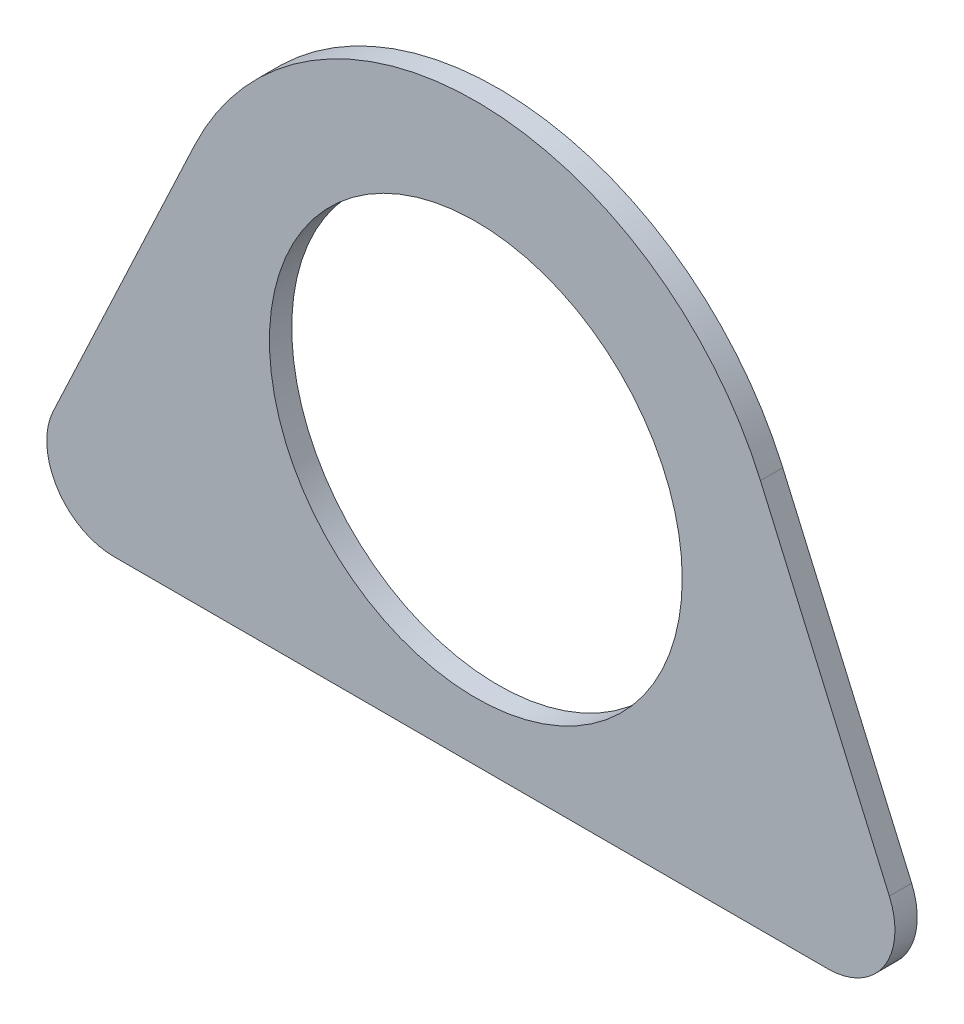
SolidWorks part; units mm, degrees
material "AISI 4340 Steel, annealed"
ref_plane "Front Plane" through (0, 0, 0) normal (0, 0, 1) x (1, 0, 0)
ref_plane "Top Plane" through (0, 0, 0) normal (0, 1, 0) x (1, 0, 0)
ref_plane "Right Plane" through (0, 0, 0) normal (1, 0, 0) x (0, 0, -1)
sketch "Sketch1" plane through (0, 0, 162) normal (0, 0, 1) x (1, 0, 0)
  line L0 (-45.305, 70) -> (-20, 70) construction
  line L1 (20, 70) -> (45.305, 70) construction
  line L2 (100.6815, -15) -> (40.766, 122.3166) construction
  line L3 (-35.2893, 123.3691) -> (-100.2791, -15) construction
  line L4 (-45.305, 70) -> (-20, 70)
  line L5 (20, 70) -> (45.305, 70)
  line L6 (58.0959, 82.5993) -> (40.766, 122.3166)
  line L7 (-35.2893, 123.3691) -> (-54.3317, 82.8261)
  line L8 (-45.305, 70) -> (-46.1855, 70)
  line L9 (-20, 70) -> (20, 70)
  line L10 (45.305, 70) -> (49.8469, 70)
  circle A0 centre (2.5, 105.6188) radius 27.75
  circle A1 centre (2.5, 105.6188) radius 31.75 construction
  circle A2 centre (2.5, 105.62) radius 31.75 construction
  arc A3 (40.766, 122.3166) -> (-35.2893, 123.3691) centre (2.5, 105.62) ccw construction
  arc A4 (40.766, 122.3166) -> (-35.2893, 123.3691) centre (2.5, 105.62) ccw
  arc A5 (49.8469, 70) -> (58.0959, 82.5993) centre (49.8469, 79) ccw
  arc A6 (-46.1855, 70) -> (-54.3317, 82.8261) centre (-46.1855, 79) cw
  dimension "D1" = 4
  dimension "D2" = 9
extrude "Boss-Extrude1" add sketch "Sketch1" along normal blind 3
